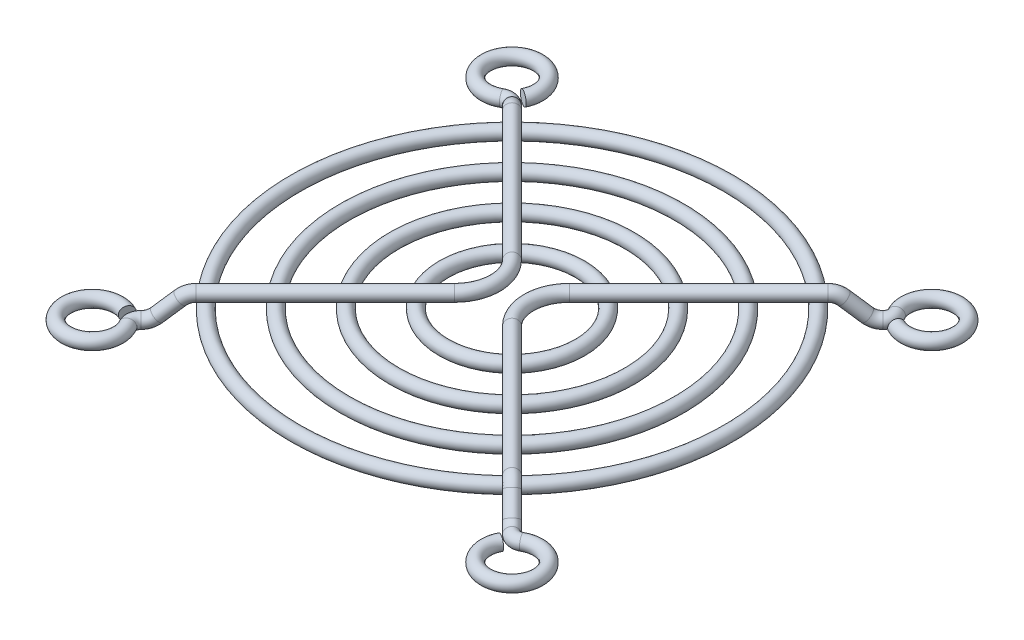
SolidWorks part; units mm, degrees
ref_plane "Front" through (0, 0, 0) normal (0, 0, 1) x (1, 0, 0)
ref_plane "Top" through (0, 0, 0) normal (0, 1, 0) x (1, 0, 0)
ref_plane "Right" through (0, 0, 0) normal (1, 0, 0) x (0, 0, -1)
sketch "Sketch1" plane through (0, 0, 0) normal (0, 0, 1) x (1, 0, 0)
  line L0 (31.79, 0) -> (-31.79, 0) construction
  line L1 (-7.3, 2) -> (7.3, 2) construction
  line L2 (-26.6, 2) -> (26.6, 2) construction
  line L3 (0, 2) -> (0, 0) construction
  line L4 (-25.8, 2) -> (-19.9, 2) construction
  line L5 (-19.9, 2) -> (-14, 2) construction
  line L6 (-14, 2) -> (-8.1, 2) construction
  circle A0 centre (-8.1, 3.6) radius 0.8 construction
  circle A1 centre (-8.1, 2) radius 0.8
  circle A2 centre (-25.8, 2) radius 0.8
  circle A3 centre (-19.9, 2) radius 0.8
  circle A4 centre (-14, 2) radius 0.8
  point P4 (-8.1, 4.4)
  dimension "D2" = 1.6
  dimension "D1" = 4.4
  dimension "D3" = 14.6
  dimension "D4" = 53.2
revolve "Revolve1" add sketch "Sketch1" angle 360 mid plane about L3
sketch "Sketch2" plane through (0, 0, 0) normal (0, 1, 0) x (1, 0, 0)
  line L0 (-18.8161, 18.8161) -> (-3.4142, 3.4142)
  line L1 (0, -2.42) -> (0, 2.42) construction
  line L2 (-2.42, 0) -> (2.42, 0) construction
  line L3 (0, 0) -> (-25, -25) construction
  arc A0 (-3.4142, 3.4142) -> (-2, 0) centre (-6.8284, 0) cw
  circle A1 centre (-2, 0) radius 0.8 construction
  circle A2 centre (0, 0) radius 26.6 construction
  circle A3 centre (-25, 25) radius 2.3 construction
  circle A4 centre (0, 0) radius 35.3553 construction
  circle A5 centre (-25, -25) radius 2.3 construction
  circle A6 centre (-25, 25) radius 3.9 construction
  point P9 (-2.8, 0)
  point P10 (-18.809, 18.809)
  dimension "D3" = 1.6
  dimension "D5" = 50
  dimension "D6" = 4.6
  dimension "D7" = 1.6
  dimension "D1" = 45
  dimension "D2" = 2.8
  dimension "D4" = 0.01
sketch "Sketch3" plane through (0, 0, 0) normal (0, 0, 1) x (1, 0, 0)
  circle A0 centre (-2, 3.6) radius 0.8
  circle A1 centre (-8.1, 3.6) radius 0.8 construction
sweep "Sweep1" add profiles "Sketch3" path "Sketch2"
ref_plane "Plane1" through (0, 0, 0) normal (0.7071, 0, -0.7071) x (-0.7071, 0, -0.7071)
sketch "Sketch4" plane through (0, 0, 0) normal (0.7071, 0, -0.7071) x (-0.7071, 0, -0.7071)
  line L0 (27.9482, 3.0863) -> (29.9171, 1.3137)
  line L3 (26.61, 2.8) -> (26.61, 4.4) construction
  line L5 (31.2553, 0.8) -> (32.2553, 0.8) construction
  line L10 (31.4553, 0) -> (33.0553, 0) construction
  arc A0 (26.61, 3.6) -> (27.9482, 3.0863) centre (26.61, 1.6) cw
  arc A1 (29.9171, 1.3137) -> (31.2553, 0.8) centre (31.2553, 2.8) ccw
  circle A2 centre (32.2553, 0.8) radius 0.8 construction
  point P9 (32.2553, 0)
  dimension "D1" = 2
  dimension "D3" = 1.6
  dimension "D2" = 1
sketch "Sketch5" plane through (-18.8161, 0, -18.8161) normal (-0.7071, 0, -0.7071) x (-0.7071, 0, 0.7071)
  circle A1 centre (0, 3.6) radius 0.8
  circle A2 centre (0, 3.6) radius 0.8
  dimension "D1" = 0
sweep "Sweep2" add profiles "Sketch5" path "Sketch4"
sketch "Sketch6" plane through (0, 0, 0) normal (0, 1, 0) x (1, 0, 0)
  line L0 (-21.5352, 22.6665) -> (-22.6665, 21.5352) construction
  line L2 (-22.2418, 23.585) -> (-25, 25) construction
  arc A0 (-23.4883, 22.2936) -> (-22.1009, 22.1009) centre (-22.922, 21.2797) cw
  arc A2 (-22.2418, 23.585) -> (-23.4883, 22.2936) centre (-25, 25) ccw
  dimension "D1" = 1.4841
sketch "Sketch7" plane through (-22.1009, 0, -22.1009) normal (-0.7071, 0, -0.7071) x (-0.7071, 0, 0.7071)
  circle A1 centre (0, 0.8) radius 0.8
  circle A2 centre (0, 0.8) radius 0.8
  dimension "D1" = 0
sweep "Sweep3" add profiles "Sketch7" path "Sketch6"
sketch "Sketch8" plane through (0, 0, 0) normal (0, 1, 0) x (1, 0, 0)
  line L0 (-3.9799, 2.8485) -> (-2.8485, 3.9799)
  line L1 (-2.8485, 3.9799) -> (-3.9799, 2.8485) construction
  line L2 (-2.8485, 3.9799) -> (-18.2504, 19.3818) construction
extrude "Cut-Extrude1" cut sketch "Sketch8" against normal through all and the other way through all flip side to cut
pattern_circular "CirPattern1" count 4 over 360 about axis through (0, 0, 0) along (0, 1, 0) of bodies 114
sketch "Sketch9" plane through (0, 0, 0) normal (0, 1, 0) x (1, 0, 0)
  line L0 (-3.9799, 2.8485) -> (-2.8485, 3.9799) construction
  line L1 (-2.8485, -3.9799) -> (-3.9799, -2.8485) construction
  arc A0 (-3.4142, 3.4142) -> (-3.4142, -3.4142) centre (-6.8284, 0) cw
sketch "Sketch10" plane through (-3.4142, 0, -3.4142) normal (0.7071, 0, 0.7071) x (0.7071, 0, -0.7071)
  circle A1 centre (0, 3.6) radius 0.8
  circle A2 centre (0, 3.6) radius 0.8
  dimension "D1" = 0
sweep "Sweep4" add profiles "Sketch10" path "Sketch9"
sketch "Sketch11" plane through (0, 0, 0) normal (0, 1, 0) x (1, 0, 0)
  line L0 (2.8485, 3.9799) -> (3.9799, 2.8485) construction
  line L1 (3.9799, -2.8485) -> (2.8485, -3.9799) construction
  arc A0 (3.4142, 3.4142) -> (3.4142, -3.4142) centre (6.8284, 0) ccw
sketch "Sketch12" plane through (3.4142, 0, -3.4142) normal (-0.7071, 0, 0.7071) x (0.7071, 0, 0.7071)
  circle A1 centre (0, 3.6) radius 0.8
  circle A2 centre (0, 3.6) radius 0.8
  dimension "D1" = 0
sweep "Sweep5" add profiles "Sketch12" path "Sketch11"
sketch "Sketch13" plane through (0, 0, 0) normal (0, 0, 1) x (1, 0, 0)
  point P0 (-28.5019, 0)
  dimension "D1" = 28.5019
sketch "Sketch14" plane through (0, 0, 0) normal (0, 1, 0) x (1, 0, 0)
  line L0 (-30, 30) -> (30, -30) construction
  line L1 (-30, 30) -> (30, 30)
  line L2 (-30, 30) -> (-30, -30)
  line L3 (-30, -30) -> (30, -30)
  line L4 (30, 30) -> (30, -30)
  circle A0 centre (0, 0) radius 26.6 construction
  circle A1 centre (0, 0) radius 25 construction
  point P4 (-26.6, 0)
  point P5 (-25, 0)
  dimension "D1" = 60
